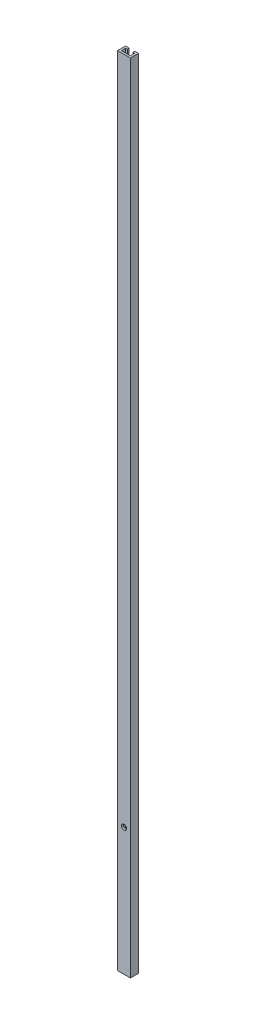
SolidWorks part; units mm, degrees
ref_plane "前视基准面" through (0, 0, 0) normal (0, 0, 1) x (1, 0, 0)
ref_plane "上视基准面" through (0, 0, 0) normal (0, 1, 0) x (1, 0, 0)
ref_plane "右视基准面" through (0, 0, 0) normal (1, 0, 0) x (0, 0, -1)
sketch "草图1" plane through (0, 0, 0) normal (0, 1, 0) x (1, 0, 0)
  line L0 (0, -5) -> (8, -5)
  line L1 (8, -5) -> (8, 0)
  line L2 (8, 0) -> (5.75, 0)
  line L3 (5.75, 0) -> (5.75, -1.15)
  line L4 (5.75, -1.15) -> (6.85, -1.15)
  line L5 (6.85, -1.15) -> (6.85, -3.85)
  line L6 (6.85, -3.85) -> (1.15, -3.85)
  line L7 (1.15, -3.85) -> (1.15, -1.15)
  line L8 (1.15, -1.15) -> (2.25, -1.15)
  line L9 (2.25, -1.15) -> (2.25, 0)
  line L10 (2.25, 0) -> (0, 0)
  line L11 (0, 0) -> (0, -5)
  line L12 (4, -3.85) -> (4, -5) construction
  line L13 (2.25, 0) -> (5.75, 0) construction
  line L14 (4, 0) -> (4, -3.85) construction
  dimension "D1" = 5
  dimension "D2" = 8
  dimension "D3" = 1.15
  dimension "D4" = 1.15
  dimension "D5" = 1.15
  dimension "D6" = 3.5
  dimension "D7" = 5.7
extrude "凸台-拉伸1" add sketch "草图1" along normal blind 500
sketch "草图2" plane through (0, 0, 5) normal (0, 0, 1) x (1, 0, 0)
  line L0 (0, 0) -> (8, 0) construction
  line L1 (4, 80) -> (4, 0) construction
  line L2 (0, 500) -> (8, 500) construction
  circle A0 centre (4, 80) radius 1.6
  dimension "D2" = 3.2
  dimension "D1" = 420
extrude "切除-拉伸1" cut sketch "草图2" against normal up to surface (1.15 mm away) up to face at (4, 250, 3.85)
